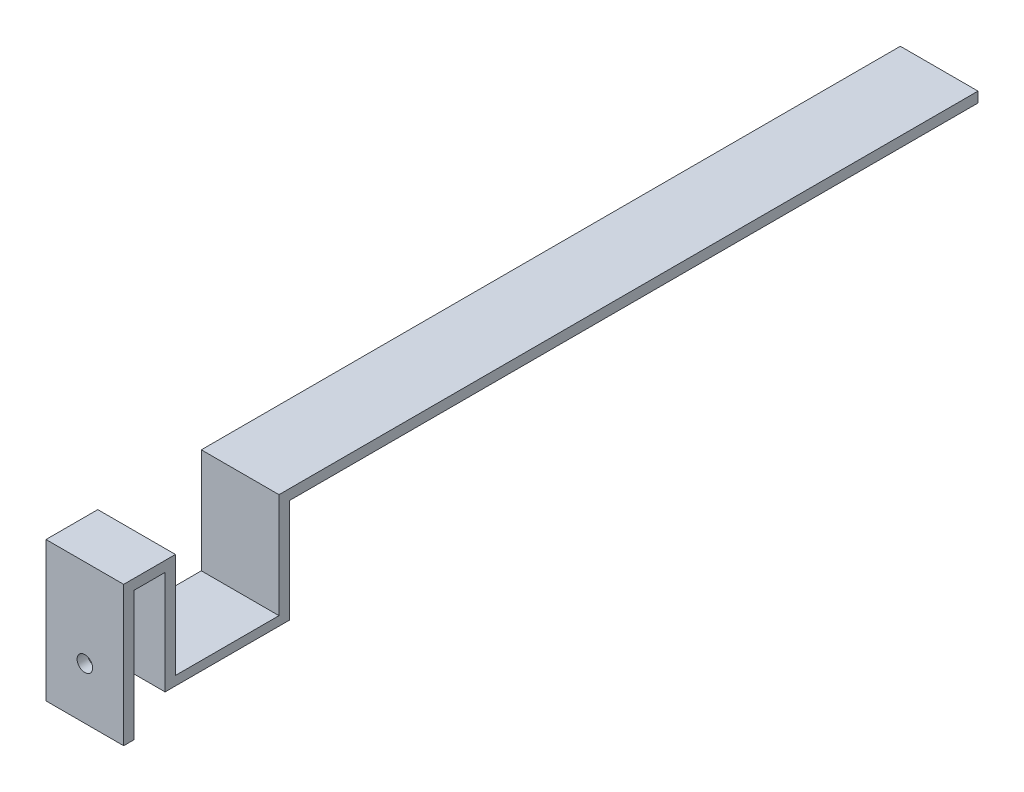
SolidWorks part; units mm, degrees
ref_plane "Front Plane" through (0, 0, 0) normal (0, 0, 1) x (1, 0, 0)
ref_plane "Top Plane" through (0, 0, 0) normal (0, 1, 0) x (1, 0, 0)
ref_plane "Right Plane" through (0, 0, 0) normal (1, 0, 0) x (0, 0, -1)
sketch "Sketch2" plane through (0, 0, 0) normal (1, 0, 0) x (0, 0, -1)
  line L0 (0, 27) -> (10, 27)
  line L1 (0, 0) -> (2, 0)
  line L2 (0, 0) -> (0, 27)
  line L4 (2, 0) -> (2, 25)
  line L7 (2, 25) -> (8, 25)
  line L9 (10, 27) -> (10, 6.7608)
  line L13 (8, 25) -> (8, 5)
  line L15 (8, 5) -> (32, 5)
  line L17 (10, 6.7608) -> (30, 6.7608)
  line L20 (32, 5) -> (32, 25)
  line L22 (30, 6.7608) -> (30, 27)
  line L23 (30, 27) -> (165, 27)
  line L25 (32, 25) -> (165, 25)
  line L26 (165, 27) -> (165, 25)
  dimension "D1" = 27
  dimension "D2" = 10
  dimension "D5" = 20
  dimension "D6" = 24
  dimension "D8" = 20
  dimension "D9" = 2
  dimension "D10" = 135
extrude "Boss-Extrude1" add sketch "Sketch2" along normal blind 15
sketch "Sketch3" plane through (0, 0, 0) normal (0, 0, 1) x (1, 0, 0)
  line L0 (15, 0) -> (0, 0) construction
  line L1 (15, 27) -> (15, 0) construction
  circle A0 centre (7.5, 10) radius 1.5
  dimension "D1" = 10
  dimension "D2" = 3
  dimension "D3" = 7.5
extrude "Cut-Extrude1" cut sketch "Sketch3" against normal blind 2
